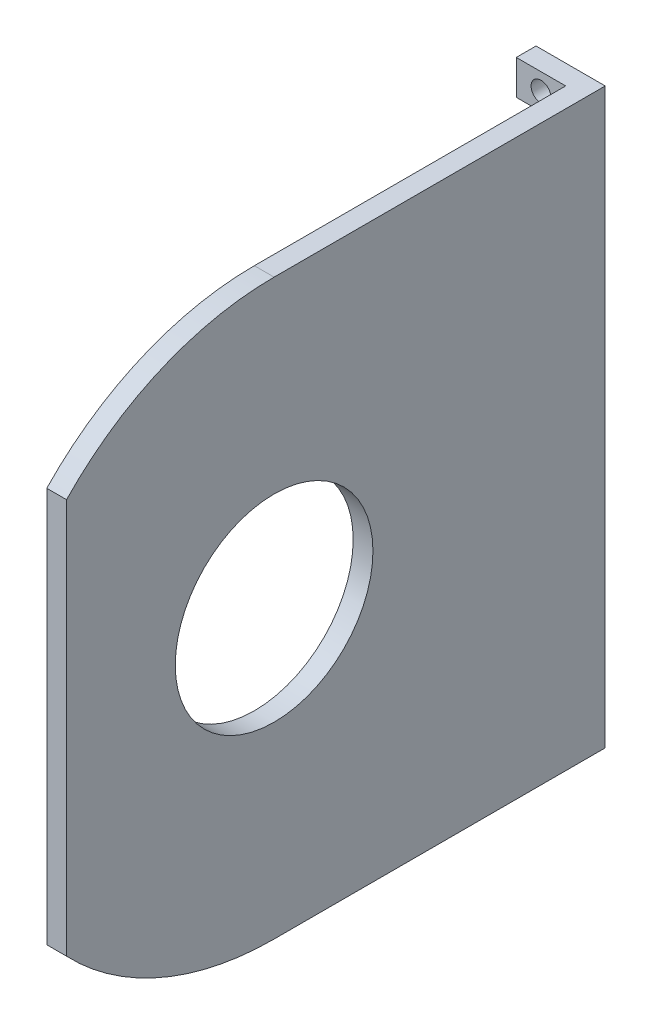
SolidWorks part; units mm, degrees
material "2024-T4"
ref_plane "Front Plane" through (0, 0, 0) normal (0, 0, 1) x (1, 0, 0)
ref_plane "Top Plane" through (0, 0, 0) normal (0, 1, 0) x (1, 0, 0)
ref_plane "Right Plane" through (0, 0, 0) normal (1, 0, 0) x (0, 0, -1)
sketch "Sketch1" plane through (0, 0, 0) normal (1, 0, 0) x (0, 0, -1)
  line L0 (62.5, 58) -> (-4.5, 58)
  line L1 (-62.5, -58) -> (62.5, -58) construction
  line L2 (-62.5, -58) -> (-62.5, 58) construction
  line L3 (-62.5, 58) -> (62.5, 58) construction
  line L4 (62.5, -58) -> (62.5, 58) construction
  line L5 (-62.5, -58) -> (62.5, 58) construction
  line L6 (-62.5, 58) -> (62.5, -58) construction
  line L7 (62.5, -58) -> (-4.5, -58)
  line L8 (62.5, -58) -> (62.5, 58)
  arc A0 (-4.5, 58) -> (-4.5, -58) centre (-4.5, 0) ccw
  circle A2 centre (-4.5, 0) radius 12
  point P0 (0, 0)
  dimension "D3" = 116
  dimension "D4" = 24
  dimension "D1" = 125
  dimension "D2" = 116
extrude "Boss-Extrude1" add sketch "Sketch1" along normal blind 4
sketch "Sketch2" [suppressed] plane through (4, 0, 0) normal (1, 0, 0) x (0, 0, -1)
  circle A0 centre (-4.5, 0) radius 13.5
  circle A1 centre (-4.5, 0) radius 12 construction
  dimension "D1" = 27
extrude "Cut-Extrude1" [suppressed] cut sketch "Sketch2" against normal blind 2
sketch "Sketch4" plane through (0, 0, 0) normal (-1, 0, 0) x (0, 0, 1)
  circle A0 centre (4.5, 0) radius 13.5
  circle A1 centre (4.5, 0) radius 12 construction
  dimension "D1" = 27
extrude "Cut-Extrude2" [suppressed] cut sketch "Sketch4" against normal blind 2
sketch "Sketch5" plane through (0, 0, -62.5) normal (0, 0, -1) x (-1, 0, 0)
  line L0 (-4, -58) -> (-4, 58) construction
  line L1 (-4, 58) -> (-14, 58)
  line L2 (-4, 58) -> (-4, 51)
  line L3 (-4, 51) -> (-14, 51)
  line L4 (-14, 58) -> (-14, 51)
  line L5 (-4, 54.5) -> (-9, 54.5) construction
  line L6 (-4, 58) -> (0, 58) construction
  line L7 (0, 0) -> (12.1764, 0) construction
  line L8 (-4, -51) -> (-14, -51)
  line L9 (-14, -58) -> (-14, -51)
  line L10 (-4, -58) -> (-14, -58)
  line L11 (-4, -58) -> (-4, -51)
  line L12 (-2, 58) -> (-2, 71.3706) construction
  line L13 (0, -58) -> (0, -51)
  line L14 (0, -58) -> (10, -58)
  line L15 (10, -58) -> (10, -51)
  line L16 (0, -51) -> (10, -51)
  line L17 (0, 51) -> (10, 51) construction
  line L18 (10, 58) -> (10, 51) construction
  line L19 (0, 58) -> (10, 58) construction
  line L20 (0, 58) -> (0, 51) construction
  circle A0 centre (-9, 54.5) radius 2
  circle A1 centre (-9, -54.5) radius 2
  circle A2 centre (5, -54.5) radius 2
  circle A3 centre (5, 54.5) radius 2 construction
  dimension "D1" = 4
  dimension "D2" = 5
  dimension "D3" = 10
  dimension "D5" = 7
  dimension "D4" = 3.5
extrude "Boss-Extrude2" [suppressed] add sketch "Sketch5" against normal blind 4
sketch "Sketch6" plane through (0, 0, -62.5) normal (0, 0, -1) x (-1, 0, 0)
  line L0 (-4, -58) -> (-4, 58) construction
  line L1 (-4, 58) -> (-14, 58)
  line L2 (-4, 58) -> (-4, 51)
  line L3 (-4, 51) -> (-14, 51)
  line L4 (-14, 58) -> (-14, 51)
  line L5 (-4, 54.5) -> (-9, 54.5) construction
  line L6 (-2, -58) -> (-2, 0) construction
  line L7 (0, 0) -> (26.903, 0) construction
  line L8 (-4, -51) -> (-14, -51)
  line L9 (-14, -58) -> (-14, -51)
  line L10 (-4, -58) -> (-14, -58)
  line L11 (-4, -58) -> (-4, -51)
  line L12 (-4, 58) -> (0, 58) construction
  line L13 (-4, -58) -> (0, -58) construction
  line L14 (0, 51) -> (10, 51) construction
  line L15 (10, 58) -> (10, 51) construction
  line L16 (0, 58) -> (10, 58) construction
  line L17 (0, 58) -> (0, 51) construction
  line L18 (0, -58) -> (0, -51) construction
  line L19 (0, -58) -> (10, -58) construction
  line L20 (10, -58) -> (10, -51) construction
  line L21 (0, -51) -> (10, -51) construction
  circle A0 centre (-9, 54.5) radius 2
  circle A1 centre (-9, -54.5) radius 2
  circle A2 centre (5, -54.5) radius 2 construction
  circle A3 centre (5, 54.5) radius 2 construction
  dimension "D1" = 4
  dimension "D2" = 5
  dimension "D3" = 10
  dimension "D4" = 7
  dimension "D5" = 3.5
extrude "Boss-Extrude3" [suppressed] add sketch "Sketch6" against normal blind 4
sketch "Sketch7" plane through (0, 0, -62.5) normal (0, 0, -1) x (-1, 0, 0)
  line L0 (0, -58) -> (0, 58) construction
  line L1 (0, 58) -> (10, 58)
  line L2 (0, 58) -> (0, 51)
  line L3 (0, 51) -> (10, 51)
  line L4 (10, 58) -> (10, 51)
  line L5 (0, 0) -> (11.9371, 0) construction
  line L6 (0, -51) -> (10, -51)
  line L7 (10, -58) -> (10, -51)
  line L8 (0, -58) -> (10, -58)
  line L9 (0, -58) -> (0, -51)
  circle A0 centre (5, 54.5) radius 2
  circle A1 centre (5, -54.5) radius 2
  dimension "D5" = 3.5
  dimension "D3" = 4
  dimension "D1" = 10
  dimension "D2" = 7
  dimension "D4" = 5
extrude "Boss-Extrude4" add sketch "Sketch7" against normal blind 4
sketch "Sketch8" plane through (0, 0, 0) normal (-1, 0, 0) x (0, 0, 1)
  circle A0 centre (4.5, 0) radius 20
  dimension "D1" = 40
extrude "Cut-Extrude3" cut sketch "Sketch8" against normal through all
sketch "Sketch9" plane through (4, 0, 0) normal (1, 0, 0) x (0, 0, -1)
  line L0 (-46.5, 40) -> (-46.5, -40)
  arc A0 (-4.5, 58) -> (-4.5, -58) centre (-4.5, 0) ccw construction
  arc A1 (-46.5, 40) -> (-46.5, -40) centre (-4.5, 0) ccw
  dimension "D1" = 80
extrude "Cut-Extrude4" cut sketch "Sketch9" against normal through all
sketch "Sketch10" [suppressed] plane through (0, 0, 0) normal (-1, 0, 0) x (0, 0, 1)
  circle A0 centre (4.5, 0) radius 27.5
  dimension "D1" = 55
extrude "Cut-Extrude5" [suppressed] cut sketch "Sketch10" against normal through all
sketch "Sketch11" [suppressed] plane through (0, 0, 0) normal (-1, 0, 0) x (0, 0, 1)
  circle A0 centre (4.5, 0) radius 29
  dimension "D1" = 58
extrude "Cut-Extrude6" [suppressed] cut sketch "Sketch11" against normal blind 2
sketch "Sketch12" [suppressed] plane through (0, 0, 0) normal (-1, 0, 0) x (0, 0, 1)
  circle A0 centre (4.5, 0) radius 32.5 construction
  circle A1 centre (4.5, 32.5) radius 2
  circle A2 centre (37, 0) radius 2
  circle A3 centre (4.5, -32.5) radius 2
  circle A4 centre (-28, 0) radius 2
  point P14 (4.5, 0)
  dimension "D1" = 65
  dimension "D2" = 4
  dimension "D3" = 4
extrude "Cut-Extrude7" [suppressed] cut sketch "Sketch12" against normal through all
sketch "Sketch13" [suppressed] plane through (0, 0, 0) normal (-1, 0, 0) x (0, 0, 1)
  circle A0 centre (4.5, 0) radius 32.5 construction
  circle A1 centre (4.5, 32.5) radius 2
  circle A2 centre (37, 0) radius 2
  circle A3 centre (4.5, -32.5) radius 2
  circle A4 centre (-28, 0) radius 2
  point P13 (4.5, 0)
  dimension "D1" = 65
  dimension "D2" = 4
  dimension "D3" = 4
extrude "Cut-Extrude8" [suppressed] cut sketch "Sketch13" against normal through all
equation "\"D4@Sketch5\"=\"D5@Sketch5\"/2"
equation "\"D5@Sketch6\"=\"D4@Sketch6\"/2"
equation "\"D5@Sketch7\"=\"D2@Sketch7\"/2"
